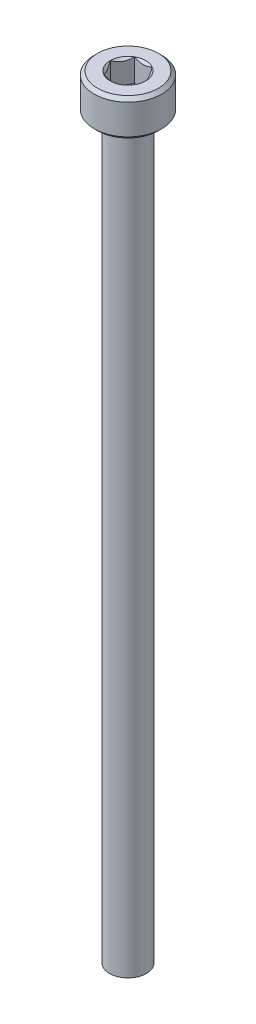
SolidWorks part; units mm, degrees
ref_plane "Front" through (0, 0, 0) normal (0, 0, 1) x (1, 0, 0)
ref_plane "Top" through (0, 0, 0) normal (0, 1, 0) x (1, 0, 0)
ref_plane "Right" through (0, 0, 0) normal (1, 0, 0) x (0, 0, -1)
sketch "Sketch1" plane through (0, 0, 0) normal (0, 1, 0) x (1, 0, 0)
  circle A0 centre (0, 0) radius 2.75
  dimension "D1" = 5.5
extrude "Boss-Extrude1" add sketch "Sketch1" along normal blind 3
sketch "Sketch2" plane through (0, 3, 0) normal (0, 1, 0) x (1, 0, 0)
  line L1 (0.7217, 1.25) -> (-0.7217, 1.25)
  line L2 (-0.7217, 1.25) -> (-1.4434, 0)
  line L3 (-1.4434, 0) -> (-0.7217, -1.25)
  line L4 (-0.7217, -1.25) -> (0.7217, -1.25)
  line L5 (0.7217, -1.25) -> (1.4434, 0)
  line L6 (1.4434, 0) -> (0.7217, 1.25)
  circle A0 centre (0, 0) radius 1.25 construction
  point P10 (0, 1.25)
  dimension "D1" = 2.5
extrude "Cut-Extrude1" cut sketch "Sketch2" against normal blind 1.88
sketch "Sketch5" plane through (0, 3, 0) normal (0, 1, 0) x (1, 0, 0)
  circle A0 centre (0, 0) radius 1.4434
extrude "Cut-Extrude2" cut sketch "Sketch5" against normal through all draft 45
chamfer "Chamfer1" distance 0.275 angle 45 2 edges at (0, 0, 2.75) (0, 3, 2.75)
sketch "草图1" plane through (0, 0, 0) normal (0, -1, 0) x (-1, 0, 0)
  circle A0 centre (0, 0) radius 1.5
  dimension "D1" = 3
extrude "凸台-拉伸1" add sketch "草图1" along normal blind 60
